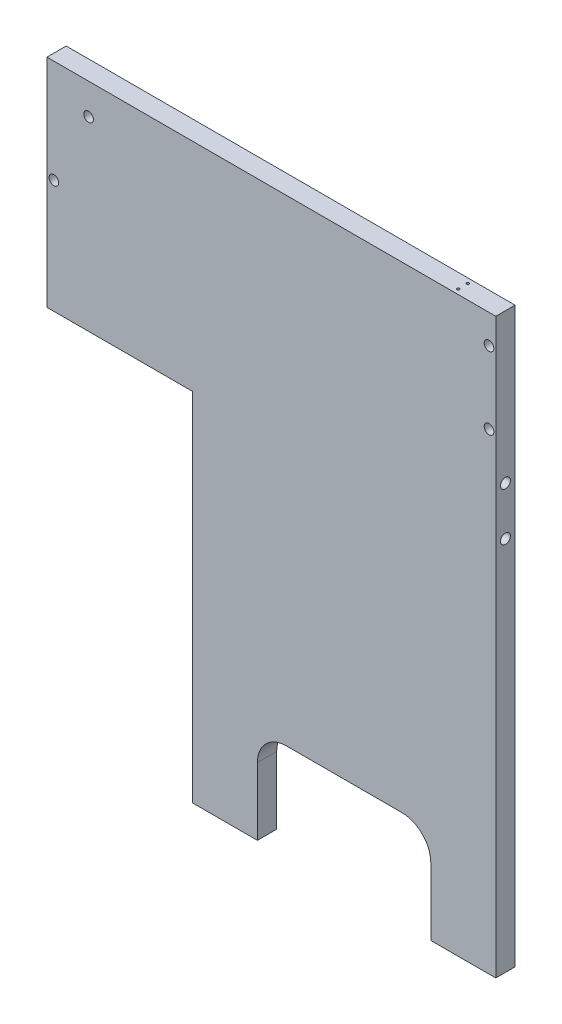
SolidWorks part; units mm, degrees
ref_plane "前视基准面" through (0, 0, 0) normal (0, 0, 1) x (1, 0, 0)
ref_plane "上视基准面" through (0, 0, 0) normal (0, 1, 0) x (1, 0, 0)
ref_plane "右视基准面" through (0, 0, 0) normal (1, 0, 0) x (0, 0, -1)
sketch "草图1" plane through (0, 0, 0) normal (0, 0, 1) x (1, 0, 0)
  line L0 (0, 0) -> (466, 0)
  line L1 (466, 0) -> (466, -595)
  line L2 (466, -595) -> (151, -595)
  line L3 (151, -595) -> (151, -225)
  line L4 (151, -225) -> (0, -225)
  line L5 (0, -225) -> (0, 0)
  dimension "D1" = 466
  dimension "D2" = 595
  dimension "D3" = 315
  dimension "D4" = 225
extrude "凸台-拉伸1" add sketch "草图1" against normal blind 20
sketch "草图2" plane through (0, 0, 0) normal (0, 0, 1) x (1, 0, 0)
  line L0 (218.5, -595) -> (218.5, -525)
  line L1 (151, -595) -> (466, -595) construction
  line L2 (248.5, -495) -> (368.5, -495)
  line L3 (398.5, -525) -> (398.5, -595)
  line L4 (398.5, -595) -> (218.5, -595)
  line L5 (466, -595) -> (466, 0) construction
  line L7 (0, 0) -> (0, -225) construction
  line L8 (466, 0) -> (0, 0) construction
  arc A0 (368.5, -495) -> (398.5, -525) centre (368.5, -525) cw
  arc A1 (218.5, -525) -> (248.5, -495) centre (248.5, -525) cw
  circle A2 centre (43.2, -32) radius 5
  circle A3 centre (459, -30) radius 5
  circle A4 centre (459, -105) radius 5
  circle A5 centre (7.2, -107) radius 5
  dimension "D1" = 30
  dimension "D5" = 43.2
  dimension "D6" = 36
  dimension "D7" = 10
  dimension "D8" = 10
  dimension "D9" = 75
  dimension "D10" = 32
  dimension "D11" = 2
  dimension "D12" = 75
  dimension "D13" = 10
  dimension "D14" = 10
  dimension "D15" = 415.8
  dimension "D2" = 180
  dimension "D3" = 100
  dimension "D4" = 67.5
extrude "切除-拉伸1" cut sketch "草图2" against normal through all
sketch "草图3" plane through (0, 0, 0) normal (-1, 0, 0) x (0, 0, 1)
  line L0 (-20, 0) -> (-20, -225) construction
  line L1 (-20, 0) -> (0, 0) construction
  circle A0 centre (-10, -155) radius 5.15
  circle A1 centre (-10, -205) radius 5.15
  point P9 (-10, 0)
  dimension "D1" = 10
  dimension "D2" = 10.3
  dimension "D3" = 10.3
  dimension "D4" = 50
  dimension "D5" = 155
extrude "切除-拉伸2" cut sketch "草图3" against normal blind 20
sketch "草图4" plane through (466, 0, 0) normal (1, 0, 0) x (0, 0, -1)
  line L0 (20, 0) -> (0, 0) construction
  line L1 (0, -595) -> (0, 0) construction
  circle A0 centre (10, -155) radius 5.15
  circle A1 centre (10, -205) radius 5.15
  dimension "D1" = 50
  dimension "D2" = 155
  dimension "D3" = 10.3
  dimension "D4" = 10.3
  dimension "D5" = 10
extrude "切除-拉伸3" cut sketch "草图4" against normal blind 20
sketch "草图5" plane through (0, 0, 0) normal (0, 1, 0) x (1, 0, 0)
  line L0 (466, 20) -> (0, 20) construction
  line L1 (466, 20) -> (466, 0) construction
  circle A0 centre (422, 15) radius 1.25
  circle A1 centre (422, 5) radius 1.25
  point P8 (0, 0)
  dimension "D1" = 2.5
  dimension "D2" = 2.5
  dimension "D3" = 10
  dimension "D4" = 5
  dimension "D5" = 44
extrude "切除-拉伸4" cut sketch "草图5" against normal blind 10
